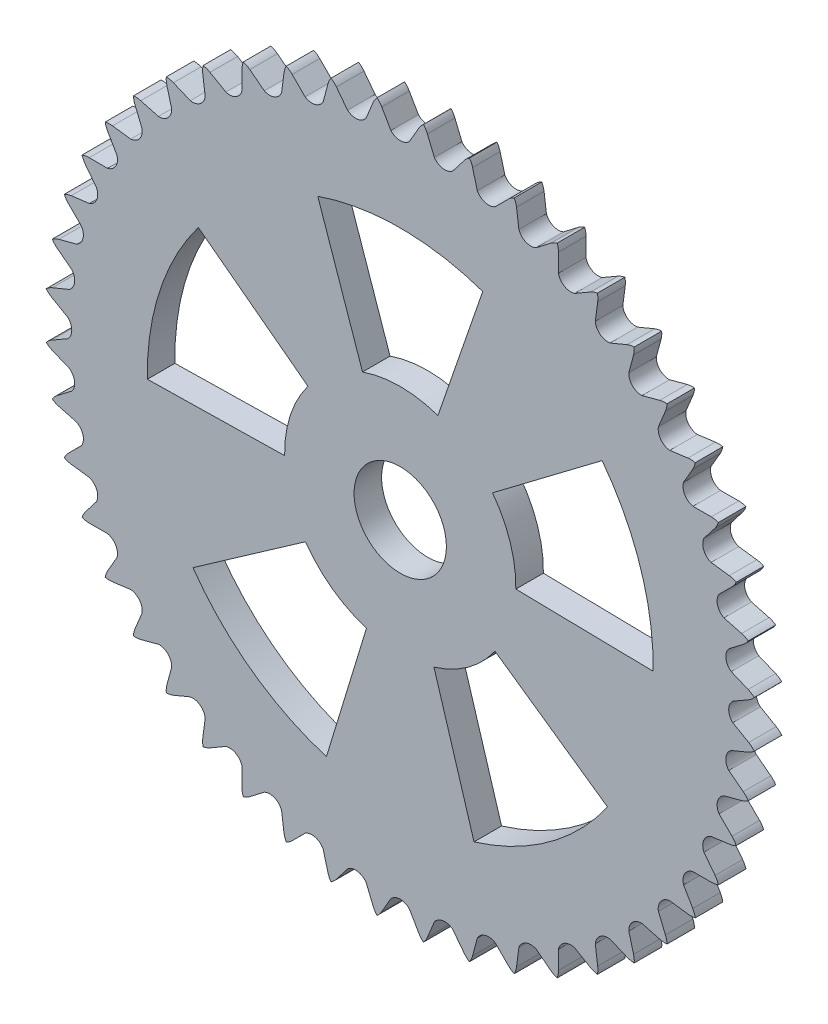
SolidWorks part; units mm, degrees
ref_plane "Front Plane" through (0, 0, 0) normal (0, 0, 1) x (1, 0, 0)
ref_plane "Top Plane" through (0, 0, 0) normal (0, 1, 0) x (1, 0, 0)
ref_plane "Right Plane" through (0, 0, 0) normal (1, 0, 0) x (0, 0, -1)
sketch "Sketch1" plane through (0, 0, 0) normal (0, 0, 1) x (1, 0, 0)
  line L0 (0, 0) -> (0, 90.91) construction
  line L1 (0, 90.91) -> (0, 94.8) construction
  line L2 (0, 94.8) -> (0, 98.27) construction
  line L3 (0, 101.9159) -> (6.5, 101.9159) construction
  line L4 (6.5, 101.9159) -> (6.5, 98.0548) construction
  line L5 (2.5897, 92.0526) -> (5.1131, 96.4427)
  line L6 (-2.5897, 92.0526) -> (-5.1131, 96.4427)
  line L7 (14.5829, 90.927) -> (17.6576, 94.9502)
  line L8 (9.4477, 91.6031) -> (7.519, 96.285)
  line L9 (26.3265, 88.2457) -> (29.9, 91.8331)
  line L10 (21.3235, 89.5863) -> (20.0224, 94.4798)
  line L11 (37.6196, 84.0545) -> (41.6309, 87.1447)
  line L12 (32.8344, 86.0366) -> (32.1832, 91.0581)
  line L13 (48.2691, 78.425) -> (52.6494, 80.9653)
  line L14 (43.7835, 81.0148) -> (43.7933, 86.0783)
  line L15 (58.0926, 71.4537) -> (62.767, 73.4005)
  line L16 (53.9835, 74.6068) -> (54.6541, 79.6258)
  line L17 (66.9222, 63.2598) -> (71.8108, 64.5798)
  line L18 (63.2598, 66.9222) -> (64.5798, 71.8108)
  line L19 (74.6068, 53.9835) -> (79.6258, 54.6541)
  line L20 (71.4537, 58.0926) -> (73.4005, 62.767)
  line L21 (81.0148, 43.7835) -> (86.0783, 43.7933)
  line L22 (78.425, 48.2691) -> (80.9653, 52.6494)
  line L23 (86.0366, 32.8344) -> (91.0581, 32.1832)
  line L24 (84.0545, 37.6196) -> (87.1447, 41.6309)
  line L25 (89.5863, 21.3235) -> (94.4798, 20.0224)
  line L26 (88.2457, 26.3265) -> (91.8331, 29.9)
  line L27 (91.6031, 9.4477) -> (96.285, 7.519)
  line L28 (90.927, 14.5829) -> (94.9502, 17.6576)
  line L29 (92.0526, -2.5897) -> (96.4427, -5.1131)
  line L30 (92.0526, 2.5897) -> (96.4427, 5.1131)
  line L31 (90.927, -14.5829) -> (94.9502, -17.6576)
  line L32 (91.6031, -9.4477) -> (96.285, -7.519)
  line L33 (88.2457, -26.3265) -> (91.8331, -29.9)
  line L34 (89.5863, -21.3235) -> (94.4798, -20.0224)
  line L35 (84.0545, -37.6196) -> (87.1447, -41.6309)
  line L36 (86.0366, -32.8344) -> (91.0581, -32.1832)
  line L37 (78.425, -48.2691) -> (80.9653, -52.6494)
  line L38 (81.0148, -43.7835) -> (86.0783, -43.7933)
  line L39 (71.4537, -58.0926) -> (73.4005, -62.767)
  line L40 (74.6068, -53.9835) -> (79.6258, -54.6541)
  line L41 (63.2598, -66.9222) -> (64.5798, -71.8108)
  line L42 (66.9222, -63.2598) -> (71.8108, -64.5798)
  line L43 (53.9835, -74.6068) -> (54.6541, -79.6258)
  line L44 (58.0926, -71.4537) -> (62.767, -73.4005)
  line L45 (43.7835, -81.0148) -> (43.7933, -86.0783)
  line L46 (48.2691, -78.425) -> (52.6494, -80.9653)
  line L47 (32.8344, -86.0366) -> (32.1832, -91.0581)
  line L48 (37.6196, -84.0545) -> (41.6309, -87.1447)
  line L49 (21.3235, -89.5863) -> (20.0224, -94.4798)
  line L50 (26.3265, -88.2457) -> (29.9, -91.8331)
  line L51 (9.4477, -91.6031) -> (7.519, -96.285)
  line L52 (14.5829, -90.927) -> (17.6576, -94.9502)
  line L53 (-2.5897, -92.0526) -> (-5.1131, -96.4427)
  line L54 (2.5897, -92.0526) -> (5.1131, -96.4427)
  line L55 (-14.5829, -90.927) -> (-17.6576, -94.9502)
  line L56 (-9.4477, -91.6031) -> (-7.519, -96.285)
  line L57 (-26.3265, -88.2457) -> (-29.9, -91.8331)
  line L58 (-21.3235, -89.5863) -> (-20.0224, -94.4798)
  line L59 (-37.6196, -84.0545) -> (-41.6309, -87.1447)
  line L60 (-32.8344, -86.0366) -> (-32.1832, -91.0581)
  line L61 (-48.2691, -78.425) -> (-52.6494, -80.9653)
  line L62 (-43.7835, -81.0148) -> (-43.7933, -86.0783)
  line L63 (-58.0926, -71.4537) -> (-62.767, -73.4005)
  line L64 (-53.9835, -74.6068) -> (-54.6541, -79.6258)
  line L65 (-66.9222, -63.2598) -> (-71.8108, -64.5798)
  line L66 (-63.2598, -66.9222) -> (-64.5798, -71.8108)
  line L67 (-74.6068, -53.9835) -> (-79.6258, -54.6541)
  line L68 (-71.4537, -58.0926) -> (-73.4005, -62.767)
  line L69 (-81.0148, -43.7835) -> (-86.0783, -43.7933)
  line L70 (-78.425, -48.2691) -> (-80.9653, -52.6494)
  line L71 (-86.0366, -32.8344) -> (-91.0581, -32.1832)
  line L72 (-84.0545, -37.6196) -> (-87.1447, -41.6309)
  line L73 (-89.5863, -21.3235) -> (-94.4798, -20.0224)
  line L74 (-88.2457, -26.3265) -> (-91.8331, -29.9)
  line L75 (-91.6031, -9.4477) -> (-96.285, -7.519)
  line L76 (-90.927, -14.5829) -> (-94.9502, -17.6576)
  line L77 (-92.0526, 2.5897) -> (-96.4427, 5.1131)
  line L78 (-92.0526, -2.5897) -> (-96.4427, -5.1131)
  line L79 (-90.927, 14.5829) -> (-94.9502, 17.6576)
  line L80 (-91.6031, 9.4477) -> (-96.285, 7.519)
  line L81 (-88.2457, 26.3265) -> (-91.8331, 29.9)
  line L82 (-89.5863, 21.3235) -> (-94.4798, 20.0224)
  line L83 (-84.0545, 37.6196) -> (-87.1447, 41.6309)
  line L84 (-86.0366, 32.8344) -> (-91.0581, 32.1832)
  line L85 (-78.425, 48.2691) -> (-80.9653, 52.6494)
  line L86 (-81.0148, 43.7835) -> (-86.0783, 43.7933)
  line L87 (-71.4537, 58.0926) -> (-73.4005, 62.767)
  line L88 (-74.6068, 53.9835) -> (-79.6258, 54.6541)
  line L89 (-63.2598, 66.9222) -> (-64.5798, 71.8108)
  line L90 (-66.9222, 63.2598) -> (-71.8108, 64.5798)
  line L91 (-53.9835, 74.6068) -> (-54.6541, 79.6258)
  line L92 (-58.0926, 71.4537) -> (-62.767, 73.4005)
  line L93 (-43.7835, 81.0148) -> (-43.7933, 86.0783)
  line L94 (-48.2691, 78.425) -> (-52.6494, 80.9653)
  line L95 (-32.8344, 86.0366) -> (-32.1832, 91.0581)
  line L96 (-37.6196, 84.0545) -> (-41.6309, 87.1447)
  line L97 (-21.3235, 89.5863) -> (-20.0224, 94.4798)
  line L98 (-26.3265, 88.2457) -> (-29.9, 91.8331)
  line L99 (-9.4477, 91.6031) -> (-7.519, 96.285)
  line L100 (-14.5829, 90.927) -> (-17.6576, 94.9502)
  arc A0 (-88.1034, 43.5292) -> (-88.1679, 43.3982) centre (0, 0) ccw construction
  arc A3 (-2.5897, 92.0526) -> (2.5897, 92.0526) centre (0, 94.4162) ccw
  arc A4 (5.1131, 96.4427) -> (6.5, 98.0548) centre (10.0254, 93.6191) cw
  arc A5 (-5.1131, 96.4427) -> (-6.5, 98.0548) centre (-10.0254, 93.6191) ccw
  arc A6 (17.6576, 94.9502) -> (19.2431, 96.3675) centre (22.1594, 91.5096) cw
  arc A7 (9.4477, 91.6031) -> (14.5829, 90.927) centre (12.3238, 93.6084) ccw
  arc A8 (7.519, 96.285) -> (6.3543, 98.0643) centre (2.2801, 94.1268) ccw
  arc A9 (29.9, 91.8331) -> (31.657, 93.0313) centre (33.9142, 87.8344) cw
  arc A10 (21.3235, 89.5863) -> (26.3265, 88.2457) centre (24.4367, 91.199) ccw
  arc A11 (20.0224, 94.4798) -> (19.0999, 96.396) centre (14.5466, 93.0239) ccw
  arc A12 (41.6309, 87.1447) -> (43.5292, 88.1034) centre (45.0888, 82.6562) cw
  arc A13 (32.8344, 86.0366) -> (37.6196, 84.0545) centre (36.1315, 87.2292) ccw
  arc A14 (32.1832, 91.0581) -> (31.5187, 93.0783) centre (26.5642, 90.3294) ccw
  arc A15 (52.6494, 80.9653) -> (54.6566, 81.6679) centre (55.4918, 76.0638) cw
  arc A16 (43.7835, 81.0148) -> (48.2691, 78.425) centre (47.2081, 81.7668) ccw
  arc A17 (43.7933, 86.0783) -> (43.3982, 88.1679) centre (38.1273, 86.0893) ccw
  arc A18 (62.767, 73.4005) -> (64.8488, 73.8352) centre (64.9454, 68.17) cw
  arc A19 (53.9835, 74.6068) -> (58.0926, 71.4537) centre (57.4769, 74.9054) ccw
  arc A20 (54.6541, 79.6258) -> (54.5352, 81.749) centre (49.038, 80.3762) ccw
  arc A21 (71.8108, 64.5798) -> (73.9314, 64.739) centre (73.2878, 59.1097) cw
  arc A22 (63.2598, 66.9222) -> (66.9222, 63.2598) centre (66.7623, 66.7623) ccw
  arc A23 (64.5798, 71.8108) -> (64.739, 73.9314) centre (59.1097, 73.2878) ccw
  arc A24 (79.6258, 54.6541) -> (81.749, 54.5352) centre (80.3762, 49.038) cw
  arc A25 (71.4537, 58.0926) -> (74.6068, 53.9835) centre (74.9054, 57.4769) ccw
  arc A26 (73.4005, 62.767) -> (73.8352, 64.8488) centre (68.17, 64.9454) ccw
  arc A27 (86.0783, 43.7933) -> (88.1679, 43.3982) centre (86.0893, 38.1273) cw
  arc A28 (78.425, 48.2691) -> (81.0148, 43.7835) centre (81.7668, 47.2081) ccw
  arc A29 (80.9653, 52.6494) -> (81.6679, 54.6566) centre (76.0638, 55.4918) ccw
  arc A30 (91.0581, 32.1832) -> (93.0783, 31.5187) centre (90.3294, 26.5642) cw
  arc A31 (84.0545, 37.6196) -> (86.0366, 32.8344) centre (87.2292, 36.1315) ccw
  arc A32 (87.1447, 41.6309) -> (88.1034, 43.5292) centre (82.6562, 45.0888) ccw
  arc A33 (94.4798, 20.0224) -> (96.396, 19.0999) centre (93.0239, 14.5466) cw
  arc A34 (88.2457, 26.3265) -> (89.5863, 21.3235) centre (91.199, 24.4367) ccw
  arc A35 (91.8331, 29.9) -> (93.0313, 31.657) centre (87.8344, 33.9142) ccw
  arc A36 (96.285, 7.519) -> (98.0643, 6.3543) centre (94.1268, 2.2801) cw
  arc A37 (90.927, 14.5829) -> (91.6031, 9.4477) centre (93.6084, 12.3238) ccw
  arc A38 (94.9502, 17.6576) -> (96.3675, 19.2431) centre (91.5096, 22.1594) ccw
  arc A39 (96.4427, -5.1131) -> (98.0548, -6.5) centre (93.6191, -10.0254) cw
  arc A40 (92.0526, 2.5897) -> (92.0526, -2.5897) centre (94.4162, 0) ccw
  arc A41 (96.4427, 5.1131) -> (98.0548, 6.5) centre (93.6191, 10.0254) ccw
  arc A42 (94.9502, -17.6576) -> (96.3675, -19.2431) centre (91.5096, -22.1594) cw
  arc A43 (91.6031, -9.4477) -> (90.927, -14.5829) centre (93.6084, -12.3238) ccw
  arc A44 (96.285, -7.519) -> (98.0643, -6.3543) centre (94.1268, -2.2801) ccw
  arc A45 (91.8331, -29.9) -> (93.0313, -31.657) centre (87.8344, -33.9142) cw
  arc A46 (89.5863, -21.3235) -> (88.2457, -26.3265) centre (91.199, -24.4367) ccw
  arc A47 (94.4798, -20.0224) -> (96.396, -19.0999) centre (93.0239, -14.5466) ccw
  arc A48 (87.1447, -41.6309) -> (88.1034, -43.5292) centre (82.6562, -45.0888) cw
  arc A49 (86.0366, -32.8344) -> (84.0545, -37.6196) centre (87.2292, -36.1315) ccw
  arc A50 (91.0581, -32.1832) -> (93.0783, -31.5187) centre (90.3294, -26.5642) ccw
  arc A51 (80.9653, -52.6494) -> (81.6679, -54.6566) centre (76.0638, -55.4918) cw
  arc A52 (81.0148, -43.7835) -> (78.425, -48.2691) centre (81.7668, -47.2081) ccw
  arc A53 (86.0783, -43.7933) -> (88.1679, -43.3982) centre (86.0893, -38.1273) ccw
  arc A54 (73.4005, -62.767) -> (73.8352, -64.8488) centre (68.17, -64.9454) cw
  arc A55 (74.6068, -53.9835) -> (71.4537, -58.0926) centre (74.9054, -57.4769) ccw
  arc A56 (79.6258, -54.6541) -> (81.749, -54.5352) centre (80.3762, -49.038) ccw
  arc A57 (64.5798, -71.8108) -> (64.739, -73.9314) centre (59.1097, -73.2878) cw
  arc A58 (66.9222, -63.2598) -> (63.2598, -66.9222) centre (66.7623, -66.7623) ccw
  arc A59 (71.8108, -64.5798) -> (73.9314, -64.739) centre (73.2878, -59.1097) ccw
  arc A60 (54.6541, -79.6258) -> (54.5352, -81.749) centre (49.038, -80.3762) cw
  arc A61 (58.0926, -71.4537) -> (53.9835, -74.6068) centre (57.4769, -74.9054) ccw
  arc A62 (62.767, -73.4005) -> (64.8488, -73.8352) centre (64.9454, -68.17) ccw
  arc A63 (43.7933, -86.0783) -> (43.3982, -88.1679) centre (38.1273, -86.0893) cw
  arc A64 (48.2691, -78.425) -> (43.7835, -81.0148) centre (47.2081, -81.7668) ccw
  arc A65 (52.6494, -80.9653) -> (54.6566, -81.6679) centre (55.4918, -76.0638) ccw
  arc A66 (32.1832, -91.0581) -> (31.5187, -93.0783) centre (26.5642, -90.3294) cw
  arc A67 (37.6196, -84.0545) -> (32.8344, -86.0366) centre (36.1315, -87.2292) ccw
  arc A68 (41.6309, -87.1447) -> (43.5292, -88.1034) centre (45.0888, -82.6562) ccw
  arc A69 (20.0224, -94.4798) -> (19.0999, -96.396) centre (14.5466, -93.0239) cw
  arc A70 (26.3265, -88.2457) -> (21.3235, -89.5863) centre (24.4367, -91.199) ccw
  arc A71 (29.9, -91.8331) -> (31.657, -93.0313) centre (33.9142, -87.8344) ccw
  arc A72 (7.519, -96.285) -> (6.3543, -98.0643) centre (2.2801, -94.1268) cw
  arc A73 (14.5829, -90.927) -> (9.4477, -91.6031) centre (12.3238, -93.6084) ccw
  arc A74 (17.6576, -94.9502) -> (19.2431, -96.3675) centre (22.1594, -91.5096) ccw
  arc A75 (-5.1131, -96.4427) -> (-6.5, -98.0548) centre (-10.0254, -93.6191) cw
  arc A76 (2.5897, -92.0526) -> (-2.5897, -92.0526) centre (0, -94.4162) ccw
  arc A77 (5.1131, -96.4427) -> (6.5, -98.0548) centre (10.0254, -93.6191) ccw
  arc A78 (-17.6576, -94.9502) -> (-19.2431, -96.3675) centre (-22.1594, -91.5096) cw
  arc A79 (-9.4477, -91.6031) -> (-14.5829, -90.927) centre (-12.3238, -93.6084) ccw
  arc A80 (-7.519, -96.285) -> (-6.3543, -98.0643) centre (-2.2801, -94.1268) ccw
  arc A81 (-29.9, -91.8331) -> (-31.657, -93.0313) centre (-33.9142, -87.8344) cw
  arc A82 (-21.3235, -89.5863) -> (-26.3265, -88.2457) centre (-24.4367, -91.199) ccw
  arc A83 (-20.0224, -94.4798) -> (-19.0999, -96.396) centre (-14.5466, -93.0239) ccw
  arc A84 (-41.6309, -87.1447) -> (-43.5292, -88.1034) centre (-45.0888, -82.6562) cw
  arc A85 (-32.8344, -86.0366) -> (-37.6196, -84.0545) centre (-36.1315, -87.2292) ccw
  arc A86 (-32.1832, -91.0581) -> (-31.5187, -93.0783) centre (-26.5642, -90.3294) ccw
  arc A87 (-52.6494, -80.9653) -> (-54.6566, -81.6679) centre (-55.4918, -76.0638) cw
  arc A88 (-43.7835, -81.0148) -> (-48.2691, -78.425) centre (-47.2081, -81.7668) ccw
  arc A89 (-43.7933, -86.0783) -> (-43.3982, -88.1679) centre (-38.1273, -86.0893) ccw
  arc A90 (-62.767, -73.4005) -> (-64.8488, -73.8352) centre (-64.9454, -68.17) cw
  arc A91 (-53.9835, -74.6068) -> (-58.0926, -71.4537) centre (-57.4769, -74.9054) ccw
  arc A92 (-54.6541, -79.6258) -> (-54.5352, -81.749) centre (-49.038, -80.3762) ccw
  arc A93 (-71.8108, -64.5798) -> (-73.9314, -64.739) centre (-73.2878, -59.1097) cw
  arc A94 (-63.2598, -66.9222) -> (-66.9222, -63.2598) centre (-66.7623, -66.7623) ccw
  arc A95 (-64.5798, -71.8108) -> (-64.739, -73.9314) centre (-59.1097, -73.2878) ccw
  arc A96 (-79.6258, -54.6541) -> (-81.749, -54.5352) centre (-80.3762, -49.038) cw
  arc A97 (-71.4537, -58.0926) -> (-74.6068, -53.9835) centre (-74.9054, -57.4769) ccw
  arc A98 (-73.4005, -62.767) -> (-73.8352, -64.8488) centre (-68.17, -64.9454) ccw
  arc A99 (-86.0783, -43.7933) -> (-88.1679, -43.3982) centre (-86.0893, -38.1273) cw
  arc A100 (-78.425, -48.2691) -> (-81.0148, -43.7835) centre (-81.7668, -47.2081) ccw
  arc A101 (-80.9653, -52.6494) -> (-81.6679, -54.6566) centre (-76.0638, -55.4918) ccw
  arc A102 (-91.0581, -32.1832) -> (-93.0783, -31.5187) centre (-90.3294, -26.5642) cw
  arc A103 (-84.0545, -37.6196) -> (-86.0366, -32.8344) centre (-87.2292, -36.1315) ccw
  arc A104 (-87.1447, -41.6309) -> (-88.1034, -43.5292) centre (-82.6562, -45.0888) ccw
  arc A105 (-94.4798, -20.0224) -> (-96.396, -19.0999) centre (-93.0239, -14.5466) cw
  arc A106 (-88.2457, -26.3265) -> (-89.5863, -21.3235) centre (-91.199, -24.4367) ccw
  arc A107 (-91.8331, -29.9) -> (-93.0313, -31.657) centre (-87.8344, -33.9142) ccw
  arc A108 (-96.285, -7.519) -> (-98.0643, -6.3543) centre (-94.1268, -2.2801) cw
  arc A109 (-90.927, -14.5829) -> (-91.6031, -9.4477) centre (-93.6084, -12.3238) ccw
  arc A110 (-94.9502, -17.6576) -> (-96.3675, -19.2431) centre (-91.5096, -22.1594) ccw
  arc A111 (-96.4427, 5.1131) -> (-98.0548, 6.5) centre (-93.6191, 10.0254) cw
  arc A112 (-92.0526, -2.5897) -> (-92.0526, 2.5897) centre (-94.4162, 0) ccw
  arc A113 (-96.4427, -5.1131) -> (-98.0548, -6.5) centre (-93.6191, -10.0254) ccw
  arc A114 (-94.9502, 17.6576) -> (-96.3675, 19.2431) centre (-91.5096, 22.1594) cw
  arc A115 (-91.6031, 9.4477) -> (-90.927, 14.5829) centre (-93.6084, 12.3238) ccw
  arc A116 (-96.285, 7.519) -> (-98.0643, 6.3543) centre (-94.1268, 2.2801) ccw
  arc A117 (-91.8331, 29.9) -> (-93.0313, 31.657) centre (-87.8344, 33.9142) cw
  arc A118 (-89.5863, 21.3235) -> (-88.2457, 26.3265) centre (-91.199, 24.4367) ccw
  arc A119 (-94.4798, 20.0224) -> (-96.396, 19.0999) centre (-93.0239, 14.5466) ccw
  arc A120 (-87.1447, 41.6309) -> (-88.1034, 43.5292) centre (-82.6562, 45.0888) cw
  arc A121 (-86.0366, 32.8344) -> (-84.0545, 37.6196) centre (-87.2292, 36.1315) ccw
  arc A122 (-91.0581, 32.1832) -> (-93.0783, 31.5187) centre (-90.3294, 26.5642) ccw
  arc A123 (-80.9653, 52.6494) -> (-81.6524, 54.5584) centre (-76.0638, 55.4918) cw
  arc A124 (-81.0148, 43.7835) -> (-78.425, 48.2691) centre (-81.7668, 47.2081) ccw
  arc A125 (-86.0783, 43.7933) -> (-88.1679, 43.3982) centre (-86.0893, 38.1273) ccw
  arc A126 (-73.4005, 62.767) -> (-73.8352, 64.8488) centre (-68.17, 64.9454) cw
  arc A127 (-74.6068, 53.9835) -> (-71.4537, 58.0926) centre (-74.9054, 57.4769) ccw
  arc A128 (-79.6258, 54.6541) -> (-81.749, 54.5352) centre (-80.3762, 49.038) ccw
  arc A129 (-64.5798, 71.8108) -> (-64.739, 73.9314) centre (-59.1097, 73.2878) cw
  arc A130 (-66.9222, 63.2598) -> (-63.2598, 66.9222) centre (-66.7623, 66.7623) ccw
  arc A131 (-71.8108, 64.5798) -> (-73.9314, 64.739) centre (-73.2878, 59.1097) ccw
  arc A132 (-54.6541, 79.6258) -> (-54.5352, 81.749) centre (-49.038, 80.3762) cw
  arc A133 (-58.0926, 71.4537) -> (-53.9835, 74.6068) centre (-57.4769, 74.9054) ccw
  arc A134 (-62.767, 73.4005) -> (-64.8488, 73.8352) centre (-64.9454, 68.17) ccw
  arc A135 (-43.7933, 86.0783) -> (-43.3982, 88.1679) centre (-38.1273, 86.0893) cw
  arc A136 (-48.2691, 78.425) -> (-43.7835, 81.0148) centre (-47.2081, 81.7668) ccw
  arc A137 (-52.6494, 80.9653) -> (-54.6566, 81.6679) centre (-55.4918, 76.0638) ccw
  arc A138 (-32.1832, 91.0581) -> (-31.5187, 93.0783) centre (-26.5642, 90.3294) cw
  arc A139 (-37.6196, 84.0545) -> (-32.8344, 86.0366) centre (-36.1315, 87.2292) ccw
  arc A140 (-41.6309, 87.1447) -> (-43.5292, 88.1034) centre (-45.0888, 82.6562) ccw
  arc A141 (-20.0224, 94.4798) -> (-19.0999, 96.396) centre (-14.5466, 93.0239) cw
  arc A142 (-26.3265, 88.2457) -> (-21.3235, 89.5863) centre (-24.4367, 91.199) ccw
  arc A143 (-29.9, 91.8331) -> (-31.657, 93.0313) centre (-33.9142, 87.8344) ccw
  arc A144 (-7.519, 96.285) -> (-6.3543, 98.0643) centre (-2.2801, 94.1268) cw
  arc A145 (-14.5829, 90.927) -> (-9.4477, 91.6031) centre (-12.3238, 93.6084) ccw
  arc A146 (-17.6576, 94.9502) -> (-19.2431, 96.3675) centre (-22.1594, 91.5096) ccw
  circle A147 centre (0, 0) radius 12.78
  point P444 (0, 0)
  dimension "D1" = 48
extrude "Boss-Extrude2" add sketch "Sketch1" along normal blind 7.62 contours L100 A146 A141 L97 A142 L98 A143 A138 L95 A139 L96 A140 A135 L93 A136 L94 A137 A132 L91 A133 L92 A134 A129 L89 A130 L90 A131 A126 L87 A127 L88 A128 A123 L85 A124 L86 A125 A120 L83 A121 L84 A122 A117 L81 A118 L82 A119 A114 L79 A115 L80
sketch "Sketch3" plane through (0, 0, 7.62) normal (0, 0, 1) x (1, 0, 0)
  line L0 (55.8784, 42.1617) -> (25.5444, 19.2739)
  line L1 (-22.8308, 66.1722) -> (-10.4369, 30.2501)
  line L2 (22.8308, 66.1722) -> (10.4369, 30.2501)
  line L3 (69.9886, -1.265) -> (31.9948, -0.5783)
  line L4 (57.3655, -40.1148) -> (26.2242, -18.3382)
  line L5 (20.4245, -66.954) -> (9.3369, -30.6075)
  line L6 (-20.4245, -66.954) -> (-9.3369, -30.6075)
  line L7 (-57.3655, -40.1148) -> (-26.2242, -18.3382)
  line L8 (-69.9886, -1.265) -> (-31.9948, -0.5783)
  line L9 (-55.8784, 42.1617) -> (-25.5444, 19.2739)
  arc A0 (22.8308, 66.1722) -> (-22.8308, 66.1722) centre (0, 0) ccw
  arc A1 (10.4369, 30.2501) -> (-10.4369, 30.2501) centre (0, 0) ccw
  arc A2 (69.9886, -1.265) -> (55.8784, 42.1617) centre (0, 0) ccw
  arc A3 (31.9948, -0.5783) -> (25.5444, 19.2739) centre (0, 0) ccw
  arc A4 (20.4245, -66.954) -> (57.3655, -40.1148) centre (0, 0) ccw
  arc A5 (9.3369, -30.6075) -> (26.2242, -18.3382) centre (0, 0) ccw
  arc A6 (-57.3655, -40.1148) -> (-20.4245, -66.954) centre (0, 0) ccw
  arc A7 (-26.2242, -18.3382) -> (-9.3369, -30.6075) centre (0, 0) ccw
  arc A8 (-55.8784, 42.1617) -> (-69.9886, -1.265) centre (0, 0) ccw
  arc A9 (-25.5444, 19.2739) -> (-31.9948, -0.5783) centre (0, 0) ccw
  point P24 (0, 0)
  dimension "D1" = 5
extrude "Cut-Extrude1" cut sketch "Sketch3" against normal blind 7.62
ref_plane "Plane1" through (0, 0, 3.75) normal (0, 0, 1) x (1, 0, 0)
sketch "Sketch4" plane through (0, 0, 3.75) normal (0, 0, 1) x (1, 0, 0)
  line L0 (0, 0) -> (0, 12.78) construction
  circle A0 centre (0, 0) radius 12.78 construction
